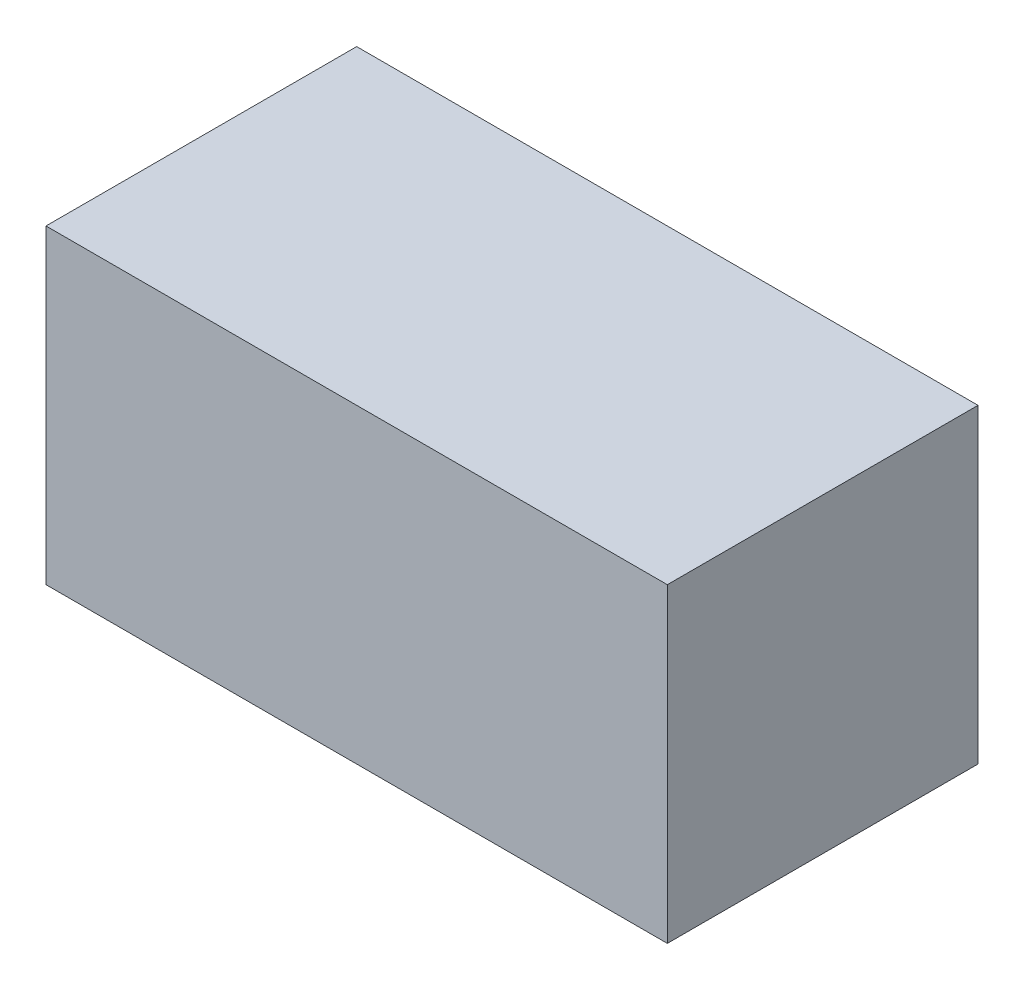
SolidWorks part; units mm, degrees
ref_plane "Front Plane" through (0, 0, 0) normal (0, 0, 1) x (1, 0, 0)
ref_plane "Top Plane" through (0, 0, 0) normal (0, 1, 0) x (1, 0, 0)
ref_plane "Right Plane" through (0, 0, 0) normal (1, 0, 0) x (0, 0, -1)
sketch "Sketch1" plane through (0, 0, 0) normal (0, 1, 0) x (1, 0, 0)
  line L1 (-487.2798, 247.5538) -> (512.7202, 247.5538)
  line L2 (-487.2798, 247.5538) -> (-487.2798, -252.4462)
  line L3 (-487.2798, -252.4462) -> (512.7202, -252.4462)
  line L4 (512.7202, 247.5538) -> (512.7202, -252.4462)
  dimension "D1" = 1000
  dimension "D2" = 500
extrude "Boss-Extrude1" add sketch "Sketch1" along normal blind 500
